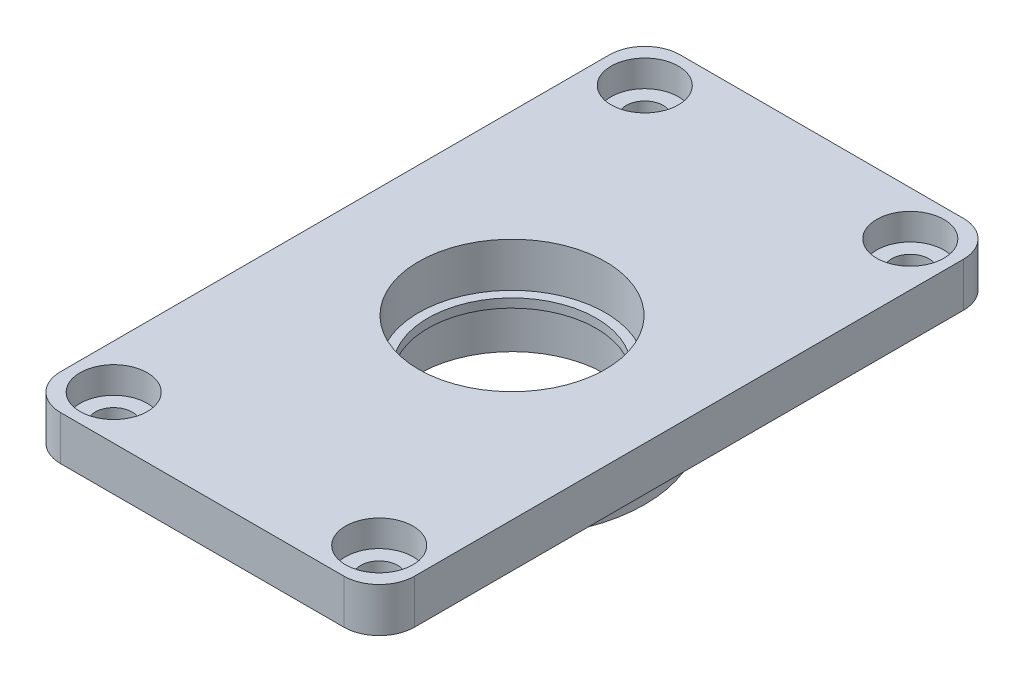
SolidWorks part; units mm, degrees
ref_plane "前视基准面" through (0, 0, 0) normal (0, 0, 1) x (1, 0, 0)
ref_plane "上视基准面" through (0, 0, 0) normal (0, 1, 0) x (1, 0, 0)
ref_plane "右视基准面" through (0, 0, 0) normal (1, 0, 0) x (0, 0, -1)
sketch "草图1" plane through (0, 0, 0) normal (0, 1, 0) x (1, 0, 0)
  line L0 (0, 0) -> (0, -58.7848) construction
  line L1 (-20, 35) -> (20, 35)
  line L2 (-20, 35) -> (-20, -35)
  line L3 (-20, -35) -> (20, -35)
  line L4 (20, 35) -> (20, -35)
  line L5 (-20, 35) -> (20, -35) construction
  line L6 (-20, -35) -> (20, 35) construction
  line L7 (0, 0) -> (35.3627, 0) construction
  line L8 (-15, -58.7848) -> (-15, 35) construction
  circle A0 centre (-15, -30) radius 2.1
  circle A1 centre (15, -30) radius 2.1
  circle A2 centre (15, 30) radius 2.1
  circle A3 centre (-15, 30) radius 2.1
  point P0 (0, 0)
  dimension "D5" = 4.2
  dimension "D1" = 70
  dimension "D2" = 40
  dimension "D3" = 5
  dimension "D4" = 5
  dimension "D6" = 60
  dimension "D7" = 30
extrude "凸台-拉伸1" add sketch "草图1" along normal blind 11
sketch "草图2" plane through (0, 11, 0) normal (0, 1, 0) x (1, 0, 0)
  circle A0 centre (0, 0) radius 9.5
  dimension "D1" = 19
extrude "切除-拉伸1" cut sketch "草图2" against normal blind 11
sketch "草图3" plane through (0, 11, 0) normal (0, 1, 0) x (1, 0, 0)
  circle A0 centre (0, 0) radius 10.55
  dimension "D1" = 21.1
extrude "切除-拉伸2" cut sketch "草图3" against normal blind 5
sketch "草图4" plane through (0, 0, 0) normal (0, -1, 0) x (1, 0, 0)
  circle A0 centre (0, 0) radius 10.55
  dimension "D1" = 21.1
extrude "切除-拉伸3" cut sketch "草图4" against normal blind 5
sketch "草图5" plane through (0, 0, 0) normal (0, -1, 0) x (1, 0, 0)
  line L0 (-20, 35) -> (20, 35) construction
  line L2 (20, -35) -> (-20, -35) construction
  line L4 (-20, 35) -> (20, 35)
  line L5 (20, 35) -> (20, -35)
  line L6 (20, -35) -> (-20, -35)
  line L7 (-20, -35) -> (-20, 35)
  circle A0 centre (0, 0) radius 15
  line M7 (20, -35) -> (20, 35)
  line M8 (20, 35) -> (-20, 35)
  line M9 (-20, 35) -> (-20, -35)
  line M10 (-20, -35) -> (20, -35)
  circle M11 centre (-15, 30) radius 2.1
  circle M12 centre (15, 30) radius 2.1
  circle M13 centre (15, -30) radius 2.1
  circle M14 centre (-15, -30) radius 2.1
  dimension "D1" = 30
extrude "切除-拉伸4" cut sketch "草图5" against normal up to surface (6 mm away) contours A0 L7 M10 M7 M14 M13 | A0 L5 M8 M9 M11 M12
sketch "草图6" plane through (0, 11, 0) normal (0, 1, 0) x (1, 0, 0)
  line L0 (0, 0) -> (-10.55, 0) construction
  line L1 (15, -30) -> (-15, -30) construction
  line L2 (15, -30) -> (15, 30) construction
  line L3 (15, 30) -> (-15, 30) construction
  line L4 (-15, -30) -> (-15, 30) construction
  line L5 (15, -30) -> (-15, 30) construction
  line L6 (15, 30) -> (-15, -30) construction
  line L7 (15, -30) -> (-15, -30) construction
  circle A0 centre (-15, 30) radius 2.1 construction
  circle A1 centre (-15, 30) radius 2.1 construction
  circle A2 centre (-15, 30) radius 3.8
  circle A3 centre (15, 30) radius 3.8
  circle A4 centre (0, 0) radius 10.55 construction
  circle A5 centre (-15, -30) radius 2.1 construction
  circle A6 centre (15, -30) radius 3.8
  circle A7 centre (-15, -30) radius 3.8
  point P3 (0, 0)
  dimension "D1" = 7.6
  dimension "D2" = 7.6
extrude "切除-拉伸5" cut sketch "草图6" against normal blind 3
fillet "圆角1" radius 4 4 edges at (-20, 8.5, 35) (20, 8.5, 35) (20, 8.5, -35) (-20, 8.5, -35)
